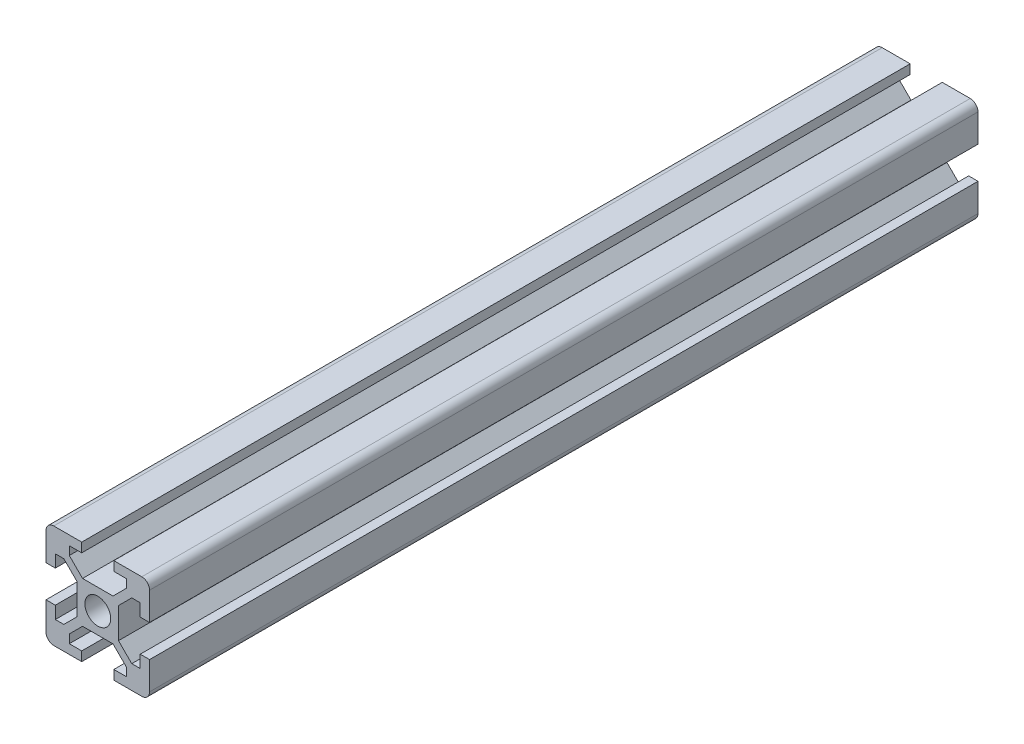
SolidWorks part; units mm, degrees
ref_plane "前视基准面" through (0, 0, 0) normal (0, 0, 1) x (1, 0, 0)
ref_plane "上视基准面" through (0, 0, 0) normal (0, 1, 0) x (1, 0, 0)
ref_plane "右视基准面" through (0, 0, 0) normal (1, 0, 0) x (0, 0, -1)
sketch "草图1" plane through (0, 0, 0) normal (0, 0, 1) x (1, 0, 0)
  line L0 (5.5, -8.2) -> (5.5, -6.5607)
  line L1 (-8.5, -10) -> (-3.1, -10)
  line L2 (-10, -8.5) -> (-10, -3.1)
  line L3 (-8.5, 10) -> (-3.1, 10)
  line L4 (10, -8.5) -> (10, -3.1)
  line L5 (-10, -10) -> (10, 10) construction
  line L6 (-10, 10) -> (10, -10) construction
  line L7 (8.2, 5.5) -> (6.5607, 5.5)
  line L8 (-2.9393, 4) -> (2.9393, 4)
  line L9 (4, 2.9393) -> (4, -2.9393)
  line L10 (2.9393, -4) -> (-2.9393, -4)
  line L11 (-4, -2.9393) -> (-4, 2.9393)
  line L12 (5.5, 6.5607) -> (5.5, 8.2)
  line L13 (6.5607, -5.5) -> (8.2, -5.5)
  line L14 (-8.2, -5.5) -> (-6.5607, -5.5)
  line L15 (-5.5, -6.5607) -> (-5.5, -8.2)
  line L16 (-5.5, 8.2) -> (-5.5, 6.5607)
  line L17 (-6.5607, 5.5) -> (-8.2, 5.5)
  line L18 (4, 2.9393) -> (6.5607, 5.5)
  line L19 (2.9393, 4) -> (5.5, 6.5607)
  line L20 (2.9393, -4) -> (5.5, -6.5607)
  line L21 (-4, 2.9393) -> (-6.5607, 5.5)
  line L22 (4, -2.9393) -> (6.5607, -5.5)
  line L23 (-2.9393, 4) -> (-5.5, 6.5607)
  line L24 (-4, -2.9393) -> (-6.5607, -5.5)
  line L25 (-2.9393, -4) -> (-5.5, -6.5607)
  line L26 (8.2, 3.1) -> (8.2, 5.5)
  line L27 (8.2, 3.1) -> (10, 3.1)
  line L28 (3.1, -8.2) -> (5.5, -8.2)
  line L29 (3.1, -8.2) -> (3.1, -10)
  line L30 (8.2, -3.1) -> (10, -3.1)
  line L31 (8.2, -3.1) -> (8.2, -5.5)
  line L32 (-3.1, -8.2) -> (-3.1, -10)
  line L33 (-3.1, -8.2) -> (-5.5, -8.2)
  line L34 (-8.2, -3.1) -> (-8.2, -5.5)
  line L35 (-8.2, -3.1) -> (-10, -3.1)
  line L36 (-8.2, 3.1) -> (-10, 3.1)
  line L37 (-8.2, 3.1) -> (-8.2, 5.5)
  line L38 (-3.1, 8.2) -> (-5.5, 8.2)
  line L39 (-3.1, 8.2) -> (-3.1, 10)
  line L40 (3.1, 8.2) -> (3.1, 10)
  line L41 (3.1, 8.2) -> (5.5, 8.2)
  line L42 (10, 3.1) -> (10, 8.5)
  line L43 (3.1, 10) -> (8.5, 10)
  line L44 (-10, 3.1) -> (-10, 8.5)
  line L45 (3.1, -10) -> (8.5, -10)
  arc A0 (8.5, -10) -> (10, -8.5) centre (8.5, -8.5) ccw
  arc A1 (-10, 8.5) -> (-8.5, 10) centre (-8.5, 8.5) cw
  arc A2 (-8.5, -10) -> (-10, -8.5) centre (-8.5, -8.5) cw
  arc A3 (8.5, 10) -> (10, 8.5) centre (8.5, 8.5) cw
  circle A4 centre (0, 0) radius 2.5
  point P0 (0, 0)
  point P39 (0, 0)
  point P56 (0, 0)
  point P73 (0, 0)
  dimension "D3" = 1.5
  dimension "D4" = 4
  dimension "D1" = 20
  dimension "D5" = 4
  dimension "D6" = 4
extrude "凸台-拉伸2" add sketch "草图1" against normal blind 160
scale "Scale1" bodies to scale 107 scale about origin uniform scaling yes scale factor 2.5
